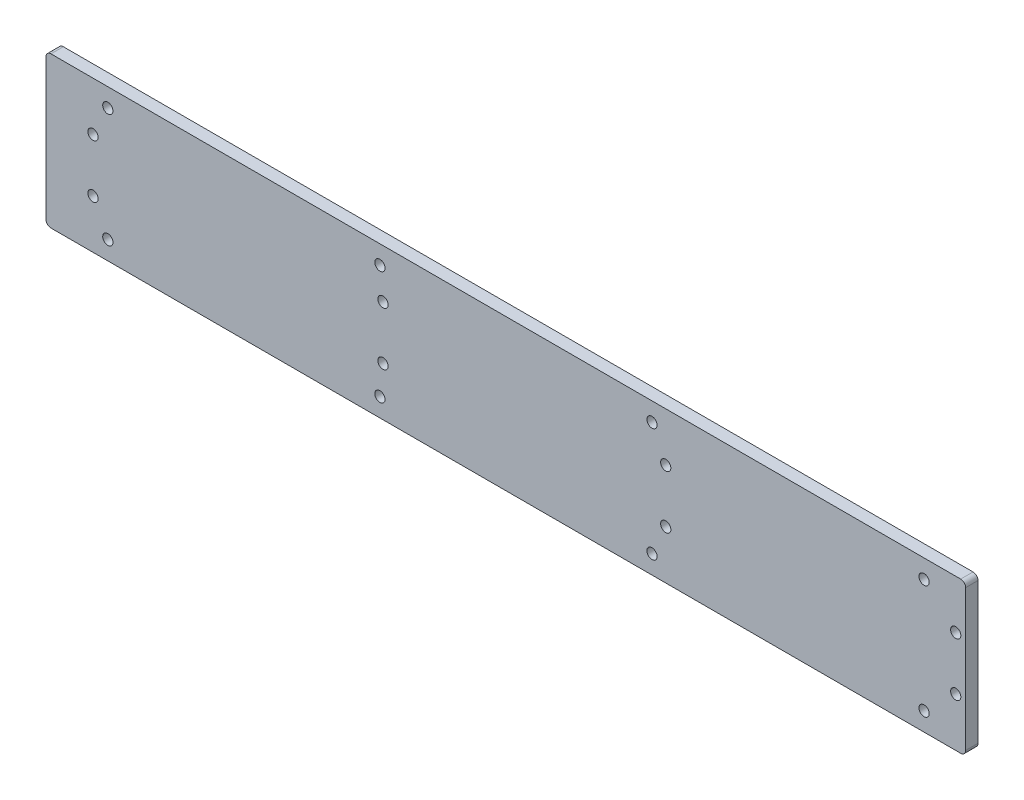
SolidWorks part; units mm, degrees
ref_plane "Alzado" through (0, 0, 0) normal (0, 0, 1) x (1, 0, 0)
ref_plane "Planta" through (0, 0, 0) normal (0, 1, 0) x (1, 0, 0)
ref_plane "Vista lateral" through (0, 0, 0) normal (1, 0, 0) x (0, 0, -1)
sketch "Croquis1" plane through (0, 0, 0) normal (0, 0, 1) x (1, 0, 0)
  line L1 (-8.795, -2.0974) -> (8.795, -2.0974)
  line L2 (-8.795, -2.0974) -> (-8.795, 2.0974)
  line L3 (-8.795, 2.0974) -> (8.795, 2.0974)
  line L4 (8.795, -2.0974) -> (8.795, 2.0974)
  line L5 (-8.795, -2.0974) -> (8.795, 2.0974) construction
  line L6 (-8.795, 2.0974) -> (8.795, -2.0974) construction
  point P0 (0, 0)
  dimension "D1" = 17.59
sketch "Croquis2" plane through (0, 0, 0) normal (0, 0, 1) x (1, 0, 0)
  line L0 (-245.618, -38.735) -> (-245.618, 38.735)
  line L1 (-226.568, -19.685) -> (226.568, -19.685) construction
  line L2 (-226.568, -19.685) -> (-226.568, 19.685) construction
  line L3 (-226.568, 19.685) -> (226.568, 19.685) construction
  line L4 (226.568, -19.685) -> (226.568, 19.685)
  line L5 (-226.568, -19.685) -> (226.568, 19.685) construction
  line L6 (-226.568, 19.685) -> (226.568, -19.685) construction
  line L7 (-245.618, 38.735) -> (226.568, 38.735)
  line L9 (-245.618, -38.735) -> (226.568, -38.735)
  line L10 (226.568, 19.685) -> (226.568, 38.735)
  line L11 (226.568, -19.685) -> (226.568, -38.735)
  line L12 (-245.618, 38.735) -> (245.618, 38.735) construction
  line L13 (245.618, -38.735) -> (245.618, 38.735) construction
  line L14 (-245.618, -38.735) -> (245.618, -38.735) construction
  point P0 (0, 0)
  dimension "D1" = 453.136
  dimension "D2" = 39.37
  dimension "D4" = 19.05
  dimension "D5" = 453.136
  dimension "D3" = 19.05
extrude "Saliente-Extruir1" add sketch "Croquis2" along normal blind 6.35
sketch "Croquis3" [suppressed] plane through (0, 0, 6.35) normal (0, 0, 1) x (1, 0, 0)
  line L0 (226.568, -38.735) -> (226.568, 38.735) construction
  line L1 (226.568, -19.685) -> (-226.568, -19.685)
  line L2 (226.568, -19.685) -> (226.568, 19.685)
  line L3 (226.568, 19.685) -> (-226.568, 19.685)
  line L4 (-226.568, -19.685) -> (-226.568, 19.685)
  line L5 (0, 0) -> (226.568, 0) construction
  line L6 (-245.618, 38.735) -> (-245.618, -38.735) construction
  line L7 (-245.618, -38.735) -> (226.568, -38.735) construction
  dimension "D1" = 19.05
  dimension "D2" = 453.136
  dimension "D3" = 19.05
  dimension "D4" = 39.37
extrude "Cortar-Extruir1" [suppressed] cut sketch "Croquis3" against normal through all
sketch "Croquis4" plane through (0, 0, 6.35) normal (0, 0, 1) x (1, 0, 0)
  line L0 (-9.525, 38.735) -> (-9.525, -38.735) construction
  line L1 (226.568, 38.735) -> (-245.618, 38.735) construction
  line L2 (-245.618, -38.735) -> (226.568, -38.735) construction
  line L3 (-221.488, 38.735) -> (-221.488, -38.735) construction
  line L4 (-245.618, 38.735) -> (-245.618, -38.735) construction
  line L5 (-245.618, 0) -> (226.568, 0) construction
  line L6 (226.568, -38.735) -> (226.568, 38.735) construction
  line L7 (-221.488, 16.3115) -> (-221.488, 11.049) construction
  line L8 (-221.488, -11.049) -> (-221.488, -16.3115) construction
  circle A0 centre (-221.488, 13.6802) radius 2.6312
  circle A1 centre (-221.488, -13.6802) radius 2.6312
  circle A2 centre (221.488, -13.6802) radius 2.6312
  circle A3 centre (221.488, 13.6802) radius 2.6312
  circle A4 centre (-72.5888, 13.6802) radius 2.6313
  circle A5 centre (-72.5888, -13.6802) radius 2.6313
  circle A6 centre (72.5888, 13.6802) radius 2.6313
  circle A7 centre (72.5888, -13.6802) radius 2.6313
  point P24 (-9.525, 0)
  dimension "D2" = 5.2625
  dimension "D1" = 24.13
  dimension "D3" = 22.098
  dimension "D4" = 148.8992
  dimension "D5" = 148.8992
  dimension "D6" = 145.1776
  dimension "D7" = 5.08
  dimension "D8" = 27.3605
  dimension "D9" = 27.3605
extrude "Cortar-Extruir2" cut sketch "Croquis4" against normal through all
sketch "Croquis5" plane through (0, 0, 6.35) normal (0, 0, 1) x (1, 0, 0)
  line L0 (226.568, 19.685) -> (-226.568, 19.685) construction
  line L1 (226.568, -38.735) -> (226.568, 38.735) construction
  line L2 (-226.568, 19.685) -> (-226.568, -19.685) construction
  line L3 (-226.568, -19.685) -> (226.568, -19.685) construction
  line L4 (226.568, 38.735) -> (-245.618, 38.735) construction
  line L5 (-245.618, -38.735) -> (226.568, -38.735) construction
  line L6 (-245.618, 38.735) -> (-245.618, -38.735) construction
  line L7 (0, 38.735) -> (0, 19.685) construction
  line L8 (-226.568, 19.685) -> (-226.568, 38.735) construction
  line L9 (-226.568, 29.21) -> (226.568, 29.21) construction
  line L10 (-226.568, 0) -> (227.979, 0) construction
  circle A0 centre (-213.868, 29.21) radius 2.6312
  circle A1 centre (-74.168, 29.21) radius 2.6313
  circle A2 centre (65.532, 29.21) radius 2.6313
  circle A3 centre (205.232, 29.21) radius 2.6312
  circle A4 centre (205.232, -29.21) radius 2.6312
  circle A5 centre (65.532, -29.21) radius 2.6313
  circle A6 centre (-74.168, -29.21) radius 2.6313
  circle A7 centre (-213.868, -29.21) radius 2.6312
  dimension "D4" = 5.2625
  dimension "D1" = 19.05
  dimension "D2" = 19.05
  dimension "D3" = 19.05
  dimension "D5" = 12.7
  dimension "D7" = 139.7
  dimension "D6" = 4
extrude "Cortar-Extruir3" cut sketch "Croquis5" against normal through all
fillet "Redondeo1" radius 2.54 4 edges at (226.568, -38.735, 3.175) (226.568, 38.735, 3.175) (-245.618, -38.735, 3.175) (-245.618, 38.735, 3.175)
fillet "Redondeo2" [suppressed] radius 2.54
sketch "Croquis6" [suppressed] plane through (0, 0, 6.35) normal (0, 0, 1) x (1, 0, 0)
  line L0 (-245.618, 0) -> (-226.568, 0) construction
  line L1 (-245.618, 36.195) -> (-245.618, -36.195) construction
  line L2 (-226.568, 19.685) -> (-226.568, -19.685) construction
sketch "Croquis8" plane through (0, 0, 6.35) normal (0, 0, 1) x (1, 0, 0)
  line L0 (226.568, -36.195) -> (226.568, 36.195) construction
  line L1 (-226.568, 19.685) -> (226.568, 19.685) construction
  line L2 (-226.568, 19.685) -> (-226.568, -19.685) construction
  line L3 (-226.568, -19.685) -> (226.568, -19.685) construction
  line L4 (226.568, 19.685) -> (226.568, -19.685) construction
  line L5 (0, 0) -> (-226.568, 0) construction
  line L6 (-245.618, 36.195) -> (-245.618, -36.195) construction
  line L7 (224.028, 38.735) -> (-243.078, 38.735) construction
  circle A1 centre (-221.488, 13.6802) radius 2.6312 construction
  dimension "D2" = 39.37
  dimension "D3" = 6.0047
  dimension "D1" = 19.05
